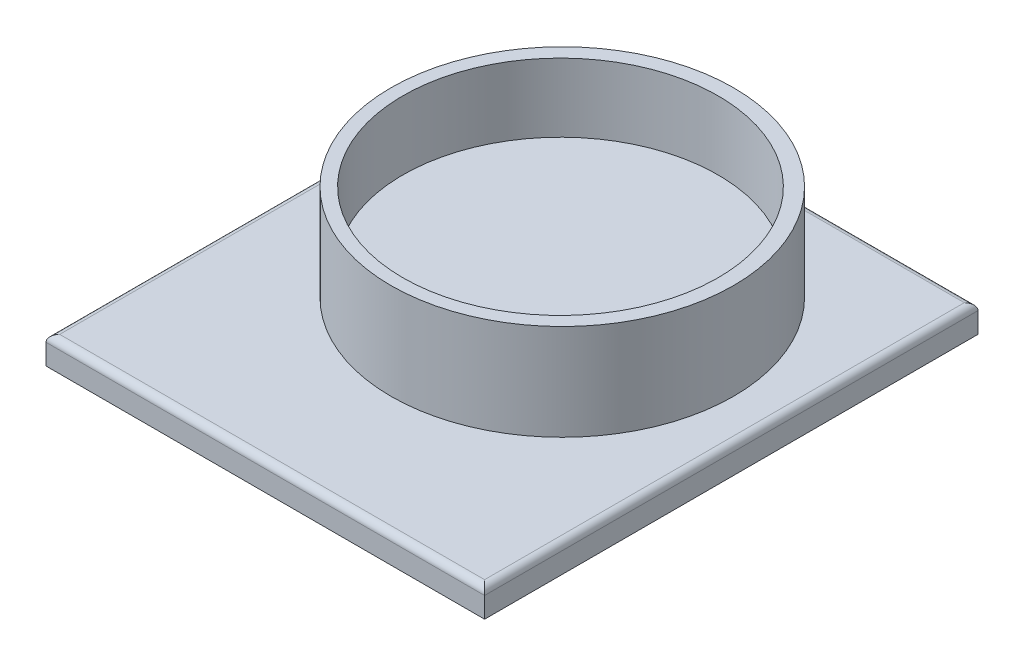
SolidWorks part; units mm, degrees
ref_plane "前视基准面" through (0, 0, 0) normal (0, 0, 1) x (1, 0, 0)
ref_plane "上视基准面" through (0, 0, 0) normal (0, 1, 0) x (1, 0, 0)
ref_plane "右视基准面" through (0, 0, 0) normal (1, 0, 0) x (0, 0, -1)
sketch "草图1" plane through (0, 0, 0) normal (0, 1, 0) x (1, 0, 0)
  line L1 (0, 0) -> (32, 0)
  line L2 (0, 0) -> (0, 36)
  line L3 (0, 36) -> (32, 36)
  line L4 (32, 0) -> (32, 36)
  dimension "D1" = 32
  dimension "D2" = 36
extrude "凸台-拉伸1" add sketch "草图1" along normal blind 2
fillet "圆角3" radius 0.5 4 edges at (16, 2, -36) (32, 2, -18) (16, 2, 0) (0, 2, -18)
sketch "草图2" plane through (0, 2, 0) normal (0, 1, 0) x (1, 0, 0)
  line L0 (31.5, 35.5) -> (0.5, 35.5) construction
  line L2 (31.5, 0.5) -> (31.5, 35.5) construction
  circle A0 centre (16.5, 21.1679) radius 12.5
  dimension "D1" = 25
  dimension "D2" = 14.3321
  dimension "D3" = 15
extrude "凸台-拉伸2" add sketch "草图2" along normal blind 7 contours A0
sketch "草图3" plane through (0, 9, 0) normal (0, 1, 0) x (1, 0, 0)
  circle A0 centre (16.4421, 21.0948) radius 11.5
  circle A1 centre (0, 24.1916) radius 0.0702
  circle A2 centre (16.5, 21.1679) radius 12.5 construction
  point P4 (0, 0)
  point P5 (0, 0)
  dimension "D1" = 23
  dimension "D2" = 0.0933
extrude "切除-拉伸1" cut sketch "草图3" against normal blind 5
